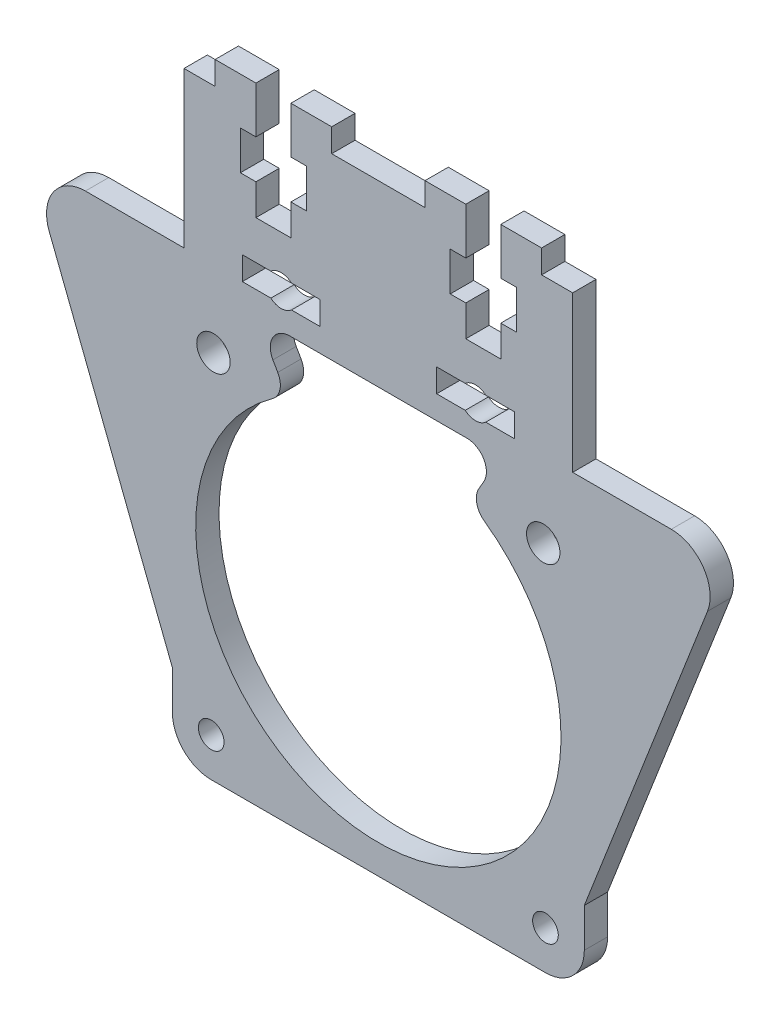
SolidWorks part; units mm, degrees
ref_plane "前视基准面" through (0, 0, 0) normal (0, 0, 1) x (1, 0, 0)
ref_plane "上视基准面" through (0, 0, 0) normal (0, 1, 0) x (1, 0, 0)
ref_plane "右视基准面" through (0, 0, 0) normal (1, 0, 0) x (0, 0, -1)
sketch "草图1" plane through (0, 0, 0) normal (0, 0, 1) x (1, 0, 0)
  line L1 (-26.5, 27.25) -> (26.5, 27.25)
  line L2 (-26.5, 27.25) -> (-26.5, -27.25)
  line L3 (-26.5, -27.25) -> (26.5, -27.25)
  line L4 (26.5, 27.25) -> (26.5, -27.25)
  line L5 (-26.5, 27.25) -> (26.5, -27.25) construction
  line L6 (-26.5, -27.25) -> (26.5, 27.25) construction
  circle A0 centre (0, 0) radius 23.5
  point P0 (0, 0)
  dimension "D3" = 47
  dimension "D1" = 54.5
  dimension "D2" = 53
extrude "凸台-拉伸1" add sketch "草图1" along normal mid plane 3
sketch "草图2" plane through (0, 0, -1.5) normal (0, 0, -1) x (-1, 0, 0)
  circle A0 centre (-21.5, -22.25) radius 1.65 construction
  circle A1 centre (-21.2132, 20.4632) radius 2.15 construction
  circle A2 centre (21.5, -22.25) radius 1.65 construction
  circle A3 centre (21.2132, 20.4632) radius 2.15 construction
  circle A4 centre (-21.5, -22.25) radius 1.65
  circle A5 centre (-21.2132, 20.4632) radius 2.15
  circle A6 centre (21.5, -22.25) radius 1.65
  circle A7 centre (21.2132, 20.4632) radius 2.15
extrude "切除-拉伸1" cut sketch "草图2" against normal blind 3
fillet "圆角1" radius 5 2 edges at (26.5, -27.25, 0) (-26.5, -27.25, 0)
sketch "草图3" plane through (0, 0, 1.5) normal (0, 0, 1) x (1, 0, 0)
  line L0 (0, 0) -> (15.7328, 27.25)
  line L1 (26.5, 27.25) -> (-26.5, 27.25) construction
  line L2 (0, 0) -> (-15.7328, 27.25)
  line L3 (15.7328, 27.25) -> (-15.7328, 27.25)
  dimension "D1" = 60
  dimension "D2" = 60
extrude "切除-拉伸2" cut sketch "草图3" against normal blind 5
sketch "草图4" plane through (0, 27.25, 0) normal (0, 1, 0) x (1, 0, 0)
  line L1 (-26.5, 1.5) -> (26.5, 1.5)
  line L2 (-26.5, 1.5) -> (-26.5, -1.5)
  line L3 (-26.5, -1.5) -> (26.5, -1.5)
  line L4 (26.5, 1.5) -> (26.5, -1.5)
extrude "凸台-拉伸2" add sketch "草图4" along normal blind 3
fillet "圆角2" radius 2.5 4 edges at (11.75, 20.3516, 0) (-11.75, 20.3516, 0) (-15.7328, 27.25, 0) (15.7328, 27.25, 0)
sketch "草图5" plane through (0, 0, 1.5) normal (0, 0, 1) x (1, 0, 0)
  line L0 (-26.5, -17.25) -> (-45, 30.25)
  line L1 (-26.5, 30.25) -> (-26.5, -22.25) construction
  line L2 (-45, 30.25) -> (-26.5, 30.25)
  line L3 (-21.5, -27.25) -> (21.5, -27.25) construction
  line L4 (-26.5, 30.25) -> (-26.5, -17.25)
  line L5 (0, -1.65) -> (0, 1.65) construction
  line L6 (26.5, -17.25) -> (45, 30.25)
  line L7 (26.5, 30.25) -> (26.5, -17.25)
  line L8 (45, 30.25) -> (26.5, 30.25)
  line L9 (-26.5, 30.25) -> (26.5, 30.25) construction
  line L10 (-25, 30.25) -> (25, 30.25)
  line L11 (-25, 30.25) -> (-25, 50.25)
  line L12 (-25, 50.25) -> (25, 50.25)
  line L13 (25, 30.25) -> (25, 50.25)
  dimension "D1" = 45
  dimension "D2" = 10
  dimension "D3" = 20
  dimension "D4" = 50
  dimension "D5" = 25
extrude "凸台-拉伸3" add sketch "草图5" against normal blind 3
sketch "草图6" plane through (0, 0, 1.5) normal (0, 0, 1) x (1, 0, 0)
  line L0 (-45, 30.25) -> (-25, 30.25) construction
  line L1 (-17.5, 33.25) -> (-13.8229, 33.25)
  line L2 (-17.5, 33.25) -> (-17.5, 30.25)
  line L3 (-17.5, 30.25) -> (-13.8229, 30.25)
  line L4 (-7.5, 33.25) -> (-7.5, 30.25)
  line L5 (-17.5, 33.25) -> (-7.5, 30.25) construction
  line L6 (-17.5, 30.25) -> (-7.5, 33.25) construction
  line L7 (7.5, 33.25) -> (11.1771, 33.25)
  line L8 (7.5, 33.25) -> (7.5, 30.25)
  line L9 (7.5, 30.25) -> (11.1771, 30.25)
  line L10 (17.5, 33.25) -> (17.5, 30.25)
  line L11 (7.5, 33.25) -> (17.5, 30.25) construction
  line L12 (7.5, 30.25) -> (17.5, 33.25) construction
  line L13 (-11.1771, 30.25) -> (-7.5, 30.25)
  line L14 (-11.1771, 33.25) -> (-7.5, 33.25)
  line L15 (13.8229, 30.25) -> (17.5, 30.25)
  line L16 (13.8229, 33.25) -> (17.5, 33.25)
  arc A0 (-13.8229, 30.25) -> (-11.1771, 30.25) centre (-12.5, 31.75) ccw
  arc A1 (11.1771, 30.25) -> (13.8229, 30.25) centre (12.5, 31.75) ccw
  arc A2 (-11.1771, 33.25) -> (-13.8229, 33.25) centre (-12.5, 31.75) ccw
  arc A3 (13.8229, 33.25) -> (11.1771, 33.25) centre (12.5, 31.75) ccw
  point P0 (-12.5, 31.75)
  point P5 (12.5, 31.75)
  dimension "D7" = 4
  dimension "D8" = 4
  dimension "D1" = 3
  dimension "D2" = 10
  dimension "D3" = 3
  dimension "D4" = 10
  dimension "D5" = 25
  dimension "D6" = 7.5
extrude "切除-拉伸9" cut sketch "草图6" against normal blind 3 contours L14 A2 L1 L2 L3 A0 L13 L4 | L16 A3 L7 L8 L9 A1 L15 L10
fillet "圆角3" radius 5 2 edges at (-45, 30.25, 0) (45, 30.25, 0)
sketch "草图8" plane through (0, 0, 1.5) normal (0, 0, 1) x (1, 0, 0)
  line L0 (25, 50.25) -> (-25, 50.25) construction
  line L1 (-21, 50.25) -> (-6, 50.25)
  line L2 (-21, 50.25) -> (-21, 53.25)
  line L3 (-21, 53.25) -> (-6, 53.25)
  line L4 (-6, 50.25) -> (-6, 53.25)
  line L5 (-25, 50.25) -> (-25, 30.25) construction
  line L6 (21, 50.25) -> (6, 50.25)
  line L7 (21, 50.25) -> (21, 53.25)
  line L8 (21, 53.25) -> (6, 53.25)
  line L9 (6, 50.25) -> (6, 53.25)
  line L10 (25, 30.25) -> (25, 50.25) construction
  dimension "D1" = 3
  dimension "D2" = 15
  dimension "D3" = 3
  dimension "D4" = 15
  dimension "D5" = 4
  dimension "D6" = 4
extrude "凸台-拉伸4" add sketch "草图8" against normal blind 3
sketch "草图9" plane through (0, 0, 1.5) normal (0, 0, 1) x (1, 0, 0)
  line L0 (-15.75, 53.25) -> (-15.75, 47.25)
  line L1 (-6, 53.25) -> (-21, 53.25) construction
  line L2 (-15.75, 47.25) -> (-17.75, 47.25)
  line L3 (-17.75, 47.25) -> (-17.75, 42.25)
  line L4 (-17.75, 42.25) -> (-15.75, 42.25)
  line L5 (-15.75, 42.25) -> (-15.75, 38.25)
  line L6 (-15.75, 38.25) -> (-11.25, 38.25)
  line L7 (-11.25, 38.25) -> (-11.25, 42.25)
  line L8 (-11.25, 42.25) -> (-9.25, 42.25)
  line L9 (-9.25, 42.25) -> (-9.25, 47.25)
  line L10 (-9.25, 47.25) -> (-11.25, 47.25)
  line L11 (-11.25, 47.25) -> (-11.25, 53.25)
  line L12 (-11.25, 53.25) -> (-15.75, 53.25)
  line L13 (-6, 50.25) -> (-6, 53.25) construction
  line L14 (0, 50.25) -> (0, 0) construction
  line L15 (6, 50.25) -> (-6, 50.25) construction
  line L16 (11.25, 47.25) -> (11.25, 53.25)
  line L17 (9.25, 47.25) -> (11.25, 47.25)
  line L18 (9.25, 42.25) -> (9.25, 47.25)
  line L19 (11.25, 42.25) -> (9.25, 42.25)
  line L20 (11.25, 38.25) -> (11.25, 42.25)
  line L21 (15.75, 38.25) -> (11.25, 38.25)
  line L22 (15.75, 42.25) -> (15.75, 38.25)
  line L23 (17.75, 42.25) -> (15.75, 42.25)
  line L24 (17.75, 47.25) -> (17.75, 42.25)
  line L25 (15.75, 47.25) -> (17.75, 47.25)
  line L26 (15.75, 53.25) -> (15.75, 47.25)
  line L27 (11.25, 53.25) -> (15.75, 53.25)
  dimension "D1" = 6
  dimension "D2" = 2
  dimension "D3" = 5
  dimension "D4" = 2
  dimension "D5" = 4
  dimension "D6" = 4.5
  dimension "D7" = 4
  dimension "D8" = 2
  dimension "D9" = 5
  dimension "D10" = 2
  dimension "D11" = 5.25
extrude "切除-拉伸10" cut sketch "草图9" against normal blind 3
